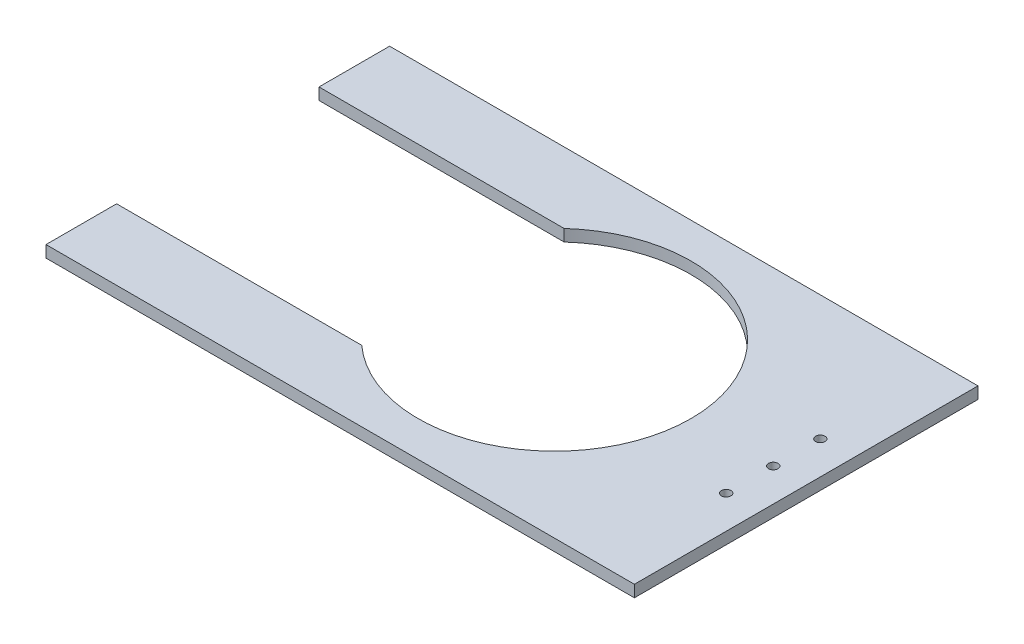
SolidWorks part; units mm, degrees
ref_plane "Front Plane" through (0, 0, 0) normal (0, 0, 1) x (1, 0, 0)
ref_plane "Top Plane" through (0, 0, 0) normal (0, 1, 0) x (1, 0, 0)
ref_plane "Right Plane" through (0, 0, 0) normal (1, 0, 0) x (0, 0, -1)
sketch "Sketch1" plane through (0, 0, 0) normal (0, 1, 0) x (1, 0, 0)
  line L0 (-118.6638, 10) -> (-118.6638, -20) construction
  line L5 (-228.6638, 10) -> (-118.6638, 10)
  line L6 (-228.6638, 10) -> (-228.6638, -20)
  line L7 (-228.6638, -20) -> (-124.5174, -20)
  line L11 (-118.6638, 10) -> (21.3362, 10)
  line L12 (21.3362, -106) -> (21.3362, 10)
  line L13 (-118.6638, -20) -> (-118.6638, -106) construction
  line L14 (-118.6638, -63) -> (-88.6227, -63) construction
  line L24 (-183.6227, -20) -> (-183.6227, -106) construction
  line L26 (21.3362, -106) -> (21.3362, -136)
  line L28 (-118.6638, -136) -> (21.3362, -136)
  line L29 (-228.6638, -136) -> (-118.6638, -136)
  line L30 (-228.6638, -136) -> (-228.6638, -106)
  line L31 (-228.6638, -106) -> (-124.5174, -106)
  line L34 (-73.6638, -20) -> (-73.6638, -106) construction
  arc A2 (-158.108, -20) -> (-209.1375, -20) centre (-183.6227, -63) ccw construction
  arc A6 (-124.5174, -106) -> (-124.5174, -20) centre (-85.5944, -63) ccw
  circle A7 centre (-183.6227, -63) radius 43 construction
  circle A8 centre (-183.6227, -63) radius 61.8136 construction
  circle A9 centre (7.3362, -63) radius 2
  circle A10 centre (7.3362, -43) radius 2
  circle A11 centre (7.3362, -83) radius 2
  point P24 (-183.6227, -63)
  dimension "D7" = 116
  dimension "D1" = 110
  dimension "D2" = 30
  dimension "D3" = 86
  dimension "D5" = 140
extrude "Boss-Extrude1" add sketch "Sketch1" along normal blind 5
sketch "Sketch3" plane through (0, 0, 20) normal (0, 0, 1) x (1, 0, 0)
  line L0 (-228.6638, 5) -> (-228.6638, 0) construction
  line L1 (-228.6638, 5) -> (-206.346, 5)
  line L2 (-228.6638, 5) -> (-228.6638, 2.5)
  line L3 (-228.6638, 2.5) -> (-206.346, 2.5)
  line L4 (-206.346, 5) -> (-206.346, 2.5)
  line L5 (-228.6638, 5) -> (-124.5174, 5) construction
  dimension "D1" = 2.5
